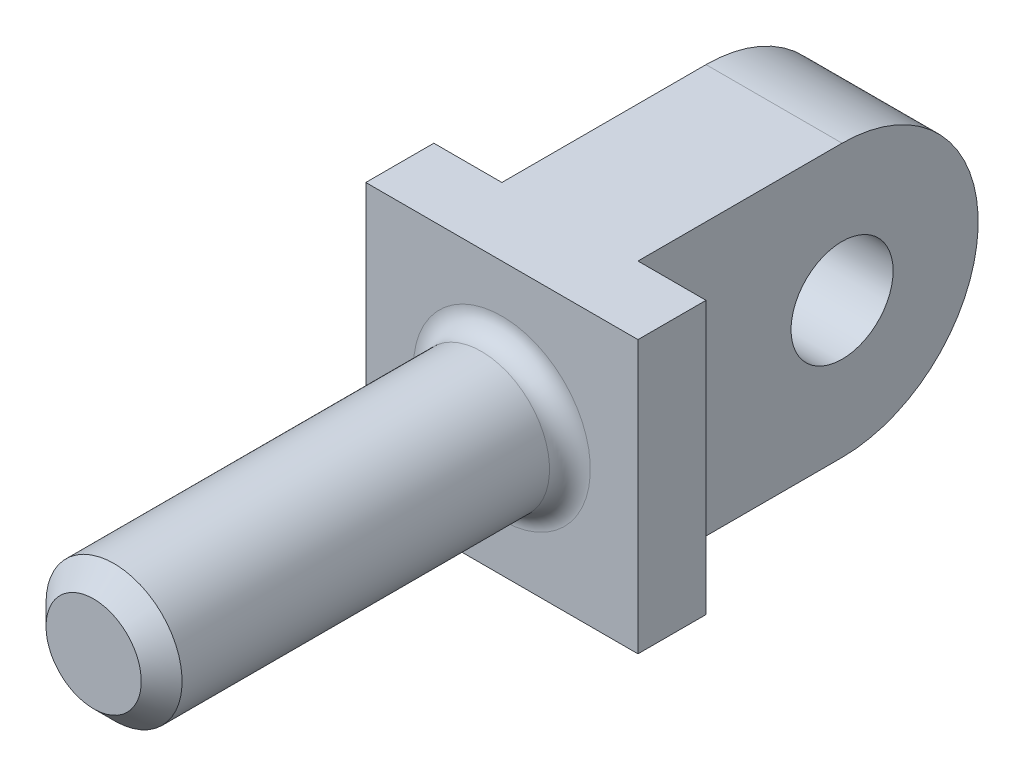
SolidWorks part; units mm, degrees
material "AISI 316 Annealed Stainless Steel Bar (SS)"
ref_plane "Front Plane" through (0, 0, 0) normal (0, 0, 1) x (1, 0, 0)
ref_plane "Top Plane" through (0, 0, 0) normal (0, 1, 0) x (1, 0, 0)
ref_plane "Right Plane" through (0, 0, 0) normal (1, 0, 0) x (0, 0, -1)
sketch "Sketch1" plane through (0, 0, 0) normal (0, 0, 1) x (1, 0, 0)
  line L1 (-25.4, -25.4) -> (25.4, -25.4)
  line L2 (-25.4, -25.4) -> (-25.4, 25.4)
  line L3 (-25.4, 25.4) -> (25.4, 25.4)
  line L4 (25.4, -25.4) -> (25.4, 25.4)
  line L5 (-25.4, -25.4) -> (25.4, 25.4) construction
  line L6 (-25.4, 25.4) -> (25.4, -25.4) construction
  point P0 (0, 0)
  dimension "D1" = 50.8
  dimension "D2" = 50.8
extrude "Square Base" add sketch "Sketch1" against normal blind 12.7
sketch "Sketch2" plane through (0, 0, 0) normal (0, 0, 1) x (1, 0, 0)
  circle A0 centre (0, 0) radius 12.7
  dimension "D1" = 25.4
extrude "Long Pin" add sketch "Sketch2" along normal blind 76.2
sketch "Sketch3" plane through (0, 0, 0) normal (1, 0, 0) x (0, 0, -1)
  line L0 (0, 0) -> (50.8, 0) construction
  line L1 (12.7, -25.4) -> (12.7, 25.4) construction
  line L2 (12.7, 25.4) -> (50.8, 25.4)
  line L3 (12.7, -25.4) -> (50.8, -25.4)
  line L4 (12.7, 25.4) -> (12.7, -25.4)
  circle A0 centre (50.8, 0) radius 9.525
  arc A1 (50.8, -25.4) -> (50.8, 25.4) centre (50.8, 0) ccw
  dimension "D1" = 19.05
  dimension "D3" = 50.8
  dimension "D2" = 38.1
extrude "Eyelet" add sketch "Sketch3" along normal mid plane 25.4
fillet "Fillet1" radius 3.81 1 edges at (-12.7, 0, 0)
chamfer "Chamfer1" distance 3.81 angle 45 1 edges at (12.7, 0, 76.2)
